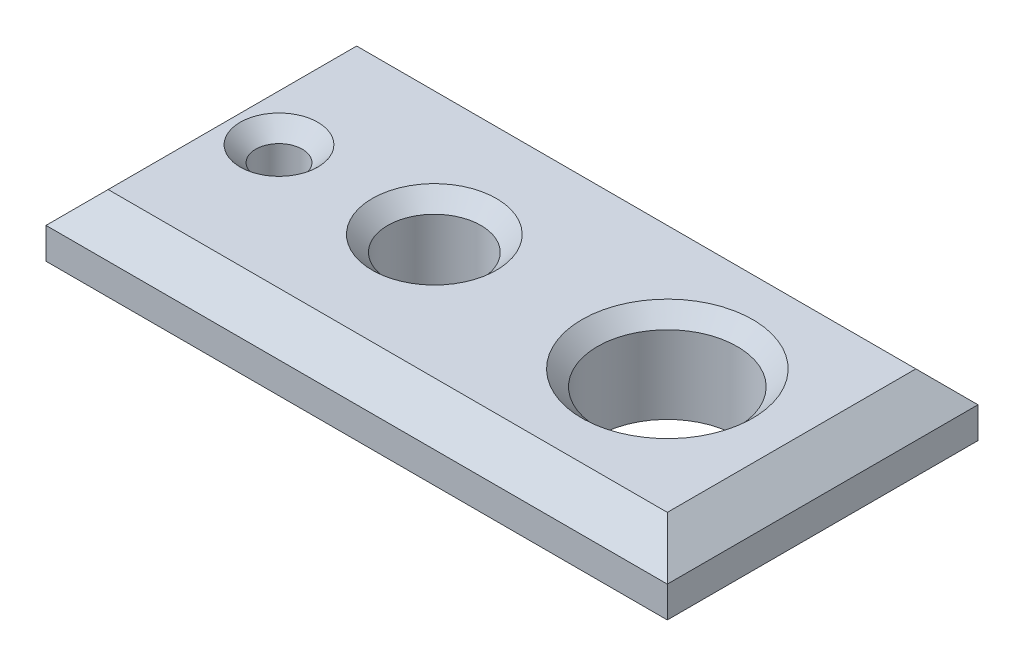
SolidWorks part; units mm, degrees
ref_plane "Alzado" through (0, 0, 0) normal (0, 0, 1) x (1, 0, 0)
ref_plane "Planta" through (0, 0, 0) normal (0, 1, 0) x (1, 0, 0)
ref_plane "Vista lateral" through (0, 0, 0) normal (1, 0, 0) x (0, 0, -1)
sketch "Croquis1" plane through (0, 0, 0) normal (0, 0, 1) x (1, 0, 0)
  line L0 (0, 0) -> (0, 30)
  line L1 (0, 30) -> (-200, 30)
  line L2 (-200, 30) -> (-200, 0)
  line L3 (-200, 0) -> (0, 0)
  dimension "D1" = 200
  dimension "D2" = 30
extrude "Saliente-Extruir1" add sketch "Croquis1" against normal blind 100
chamfer "Chaflán1" distance 10 angle 45 4 edges at (0, 0, -50) (-200, 0, -50) (-200, 30, -50) (0, 30, -50)
chamfer "Chaflán2" distance 10 angle 45 4 edges at (-100, 0, -100) (-100, 30, -100) (-100, 0, 0) (-100, 30, 0)
sketch "Croquis8" plane through (0, 30, 0) normal (0, 1, 0) x (1, 0, 0)
  line L0 (-190, 50) -> (-10, 50) construction
  line L1 (-200, 0) -> (-200, 100) construction
  line L2 (-200, 0) -> (-200, 100)
  line L3 (-175, 50) -> (-175, 10) construction
  line L4 (-10, 10) -> (-10, 90)
  line L5 (-10, 90) -> (-190, 90)
  line L6 (-190, 90) -> (-190, 10)
  line L7 (-190, 10) -> (-10, 10)
  line L8 (-10, 10) -> (-10, 90)
  line L9 (-10, 90) -> (-190, 90)
  line L10 (-190, 90) -> (-190, 10)
  line L11 (-190, 10) -> (-10, 10)
  line L12 (-125, 50) -> (-125, 10)
  line L13 (-50, 50) -> (-50, 10)
  circle A0 centre (-175, 50) radius 7.5
  circle A1 centre (-125, 50) radius 15
  circle A2 centre (-50, 50) radius 22.5
  dimension "D5" = 15
  dimension "D6" = 30
  dimension "D7" = 45
  dimension "D2" = 25
  dimension "D3" = 50
  dimension "D4" = 75
  dimension "D1" = 0
extrude "Cortar-Extruir5" cut sketch "Croquis8" against normal through all contours A0 | A1 | A2
chamfer "Chaflán4" distance 5 angle 45 3 edges at (-72.5, 30, -50) (-140, 30, -50) (-182.5, 30, -50)
